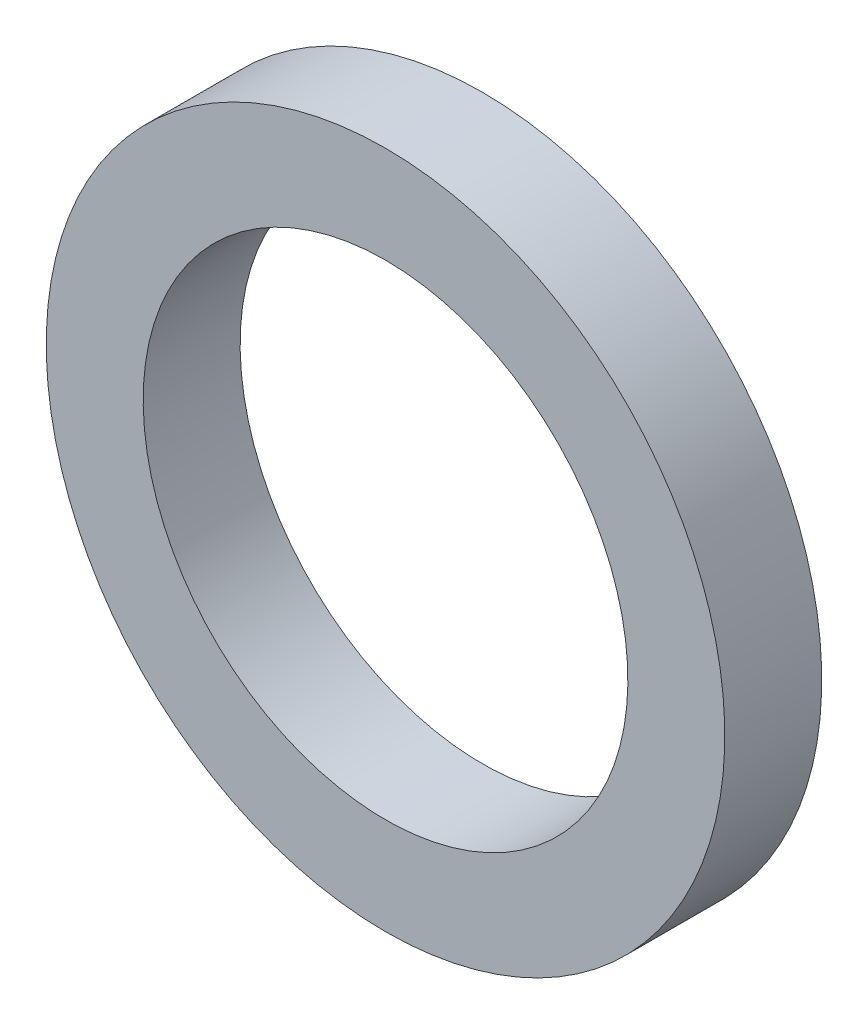
SolidWorks part; units mm, degrees
material "AISI 4130 Steel, annealed at 865C"
ref_plane "Front Plane" through (0, 0, 0) normal (0, 0, 1) x (1, 0, 0)
ref_plane "Top Plane" through (0, 0, 0) normal (0, 1, 0) x (1, 0, 0)
ref_plane "Right Plane" through (0, 0, 0) normal (1, 0, 0) x (0, 0, -1)
sketch "Sketch1" plane through (0, 0, 0) normal (1, 0, 0) x (0, 0, -1)
  line L0 (0, 12.7) -> (0, 0) construction
  line L1 (-5.08, 17.78) -> (0, 17.78)
  line L2 (-5.08, 17.78) -> (-5.08, 12.7)
  line L3 (-5.08, 12.7) -> (0, 12.7)
  line L4 (0, 17.78) -> (0, 12.7)
  line L5 (0, 0) -> (-15.2579, 0) construction
  dimension "D1" = 12.7
  dimension "D2" = 5.08
  dimension "D3" = 5.08
revolve "Revolve1" add sketch "Sketch1" angle 360 about L5
